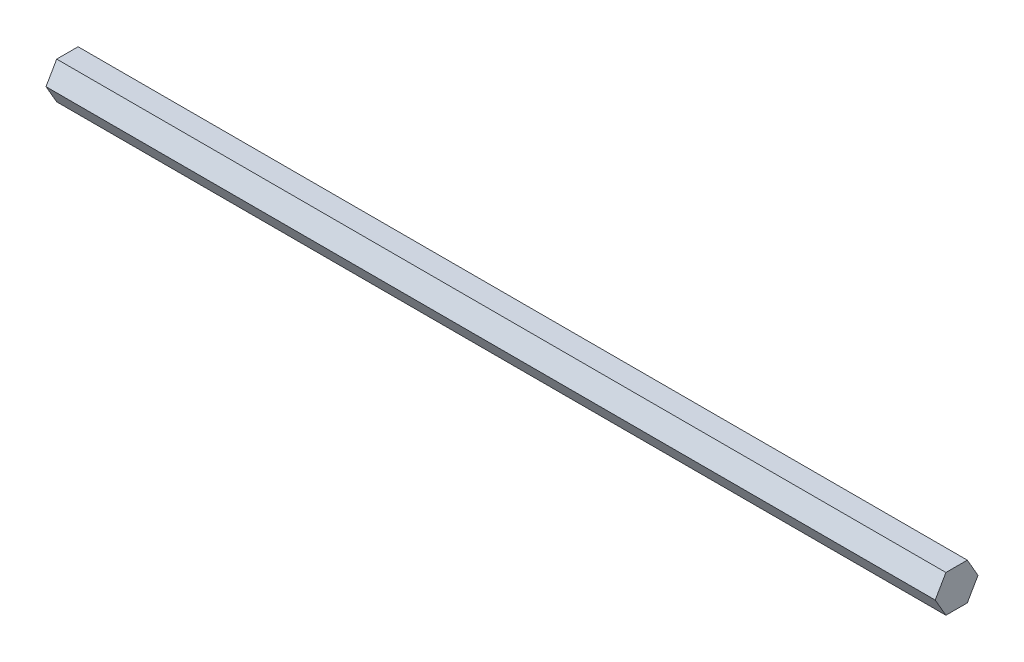
SolidWorks part; units mm, degrees
ref_plane "Front Plane" through (0, 0, 0) normal (0, 0, 1) x (1, 0, 0)
ref_plane "Top Plane" through (0, 0, 0) normal (0, 1, 0) x (1, 0, 0)
ref_plane "Right Plane" through (0, 0, 0) normal (1, 0, 0) x (0, 0, -1)
sketch "Sketch1" plane through (0, 0, 0) normal (1, 0, 0) x (0, 0, -1)
  line L1 (3.6662, 6.35) -> (-3.6662, 6.35)
  line L2 (-3.6662, 6.35) -> (-7.3323, 0)
  line L3 (-7.3323, 0) -> (-3.6662, -6.35)
  line L4 (-3.6662, -6.35) -> (3.6662, -6.35)
  line L5 (3.6662, -6.35) -> (7.3323, 0)
  line L6 (7.3323, 0) -> (3.6662, 6.35)
  circle A0 centre (0, 0) radius 6.35 construction
  dimension "D1" = 12.7
extrude "Boss-Extrude1" add sketch "Sketch1" along normal mid plane 304.8
